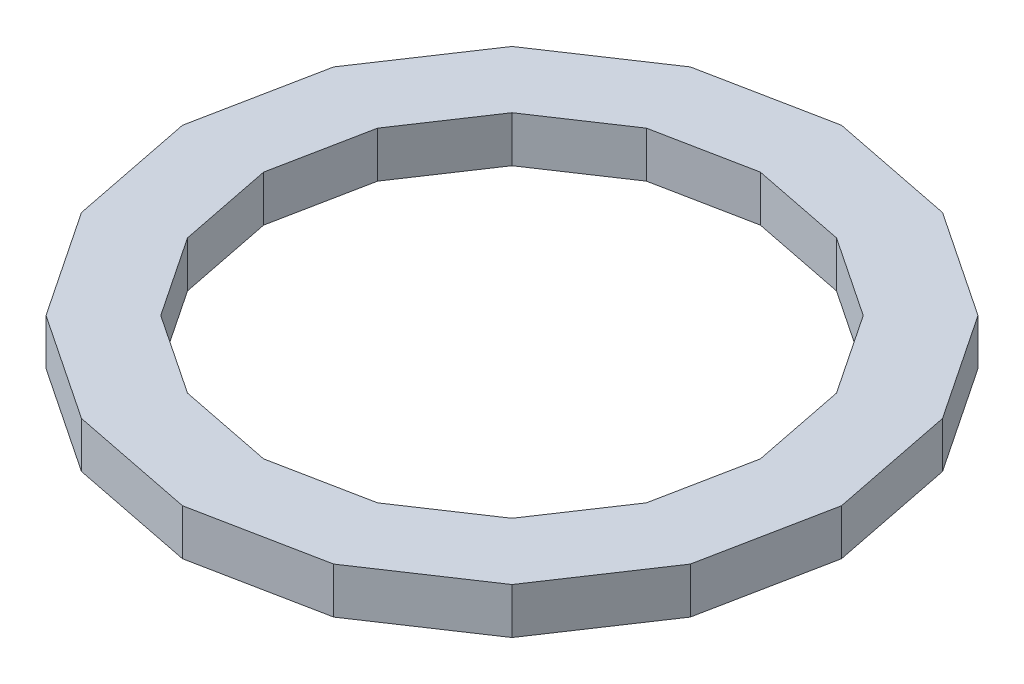
SolidWorks part; units mm, degrees
ref_plane "Front Plane" through (0, 0, 0) normal (0, 0, 1) x (1, 0, 0)
ref_plane "Top Plane" through (0, 0, 0) normal (0, 1, 0) x (1, 0, 0)
ref_plane "Right Plane" through (0, 0, 0) normal (1, 0, 0) x (0, 0, -1)
sketch "Sketch1" plane through (0, 0, 0) normal (0, 1, 0) x (1, 0, 0)
  line L1 (136.7059, 0) -> (126.2998, 52.3151)
  line L2 (126.2998, 52.3151) -> (96.6657, 96.6657)
  line L3 (96.6657, 96.6657) -> (52.3151, 126.2998)
  line L4 (52.3151, 126.2998) -> (0, 136.7059)
  line L5 (0, 136.7059) -> (-52.3151, 126.2998)
  line L6 (-52.3151, 126.2998) -> (-96.6657, 96.6657)
  line L7 (-96.6657, 96.6657) -> (-126.2998, 52.3151)
  line L8 (-126.2998, 52.3151) -> (-136.7059, 0)
  line L9 (-136.7059, 0) -> (-126.2998, -52.3151)
  line L10 (-126.2998, -52.3151) -> (-96.6657, -96.6657)
  line L11 (-96.6657, -96.6657) -> (-52.3151, -126.2998)
  line L12 (-52.3151, -126.2998) -> (0, -136.7059)
  line L13 (0, -136.7059) -> (52.3151, -126.2998)
  line L14 (52.3151, -126.2998) -> (96.6657, -96.6657)
  line L15 (96.6657, -96.6657) -> (126.2998, -52.3151)
  line L16 (126.2998, -52.3151) -> (136.7059, 0)
  line L17 (103.039, 0) -> (95.1956, 39.4313)
  line L18 (95.1956, 39.4313) -> (72.8596, 72.8596)
  line L19 (72.8596, 72.8596) -> (39.4313, 95.1956)
  line L20 (39.4313, 95.1956) -> (0, 103.039)
  line L21 (0, 103.039) -> (-39.4313, 95.1956)
  line L22 (-39.4313, 95.1956) -> (-72.8596, 72.8596)
  line L23 (-72.8596, 72.8596) -> (-95.1956, 39.4313)
  line L24 (-95.1956, 39.4313) -> (-103.039, 0)
  line L25 (-103.039, 0) -> (-95.1956, -39.4313)
  line L26 (-95.1956, -39.4313) -> (-72.8596, -72.8596)
  line L27 (-72.8596, -72.8596) -> (-39.4313, -95.1956)
  line L28 (-39.4313, -95.1956) -> (0, -103.039)
  line L29 (0, -103.039) -> (39.4313, -95.1956)
  line L30 (39.4313, -95.1956) -> (72.8596, -72.8596)
  line L31 (72.8596, -72.8596) -> (95.1956, -39.4313)
  line L32 (95.1956, -39.4313) -> (103.039, 0)
  circle A0 centre (0, 0) radius 134.0791 construction
  circle A1 centre (0, 0) radius 101.0591 construction
  dimension "D1" = 53.34
  dimension "D2" = 33.02
extrude "Boss-Extrude1" add sketch "Sketch1" along normal blind 19.05
